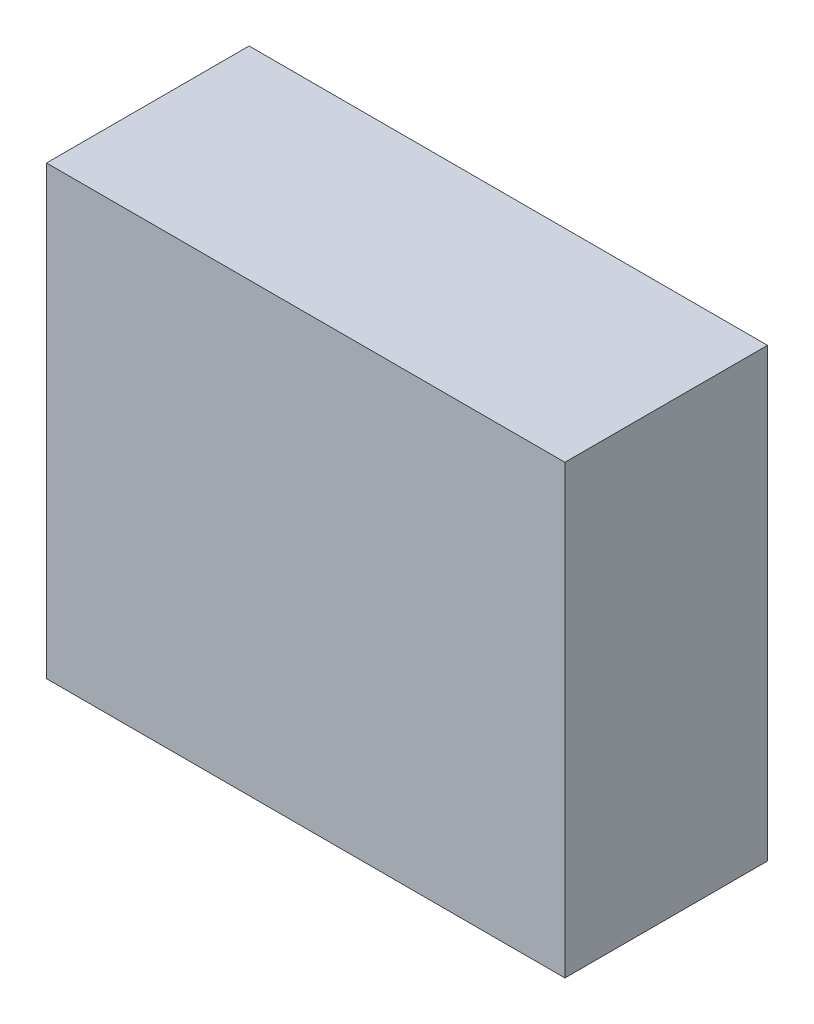
SolidWorks part; units mm, degrees
ref_plane "Front Plane" through (0, 0, 0) normal (0, 0, 1) x (1, 0, 0)
ref_plane "Top Plane" through (0, 0, 0) normal (0, 1, 0) x (1, 0, 0)
ref_plane "Right Plane" through (0, 0, 0) normal (1, 0, 0) x (0, 0, -1)
sketch "Sketch1" plane through (0, 0, 0) normal (0, 0, 1) x (1, 0, 0)
  line L1 (-32.5, 28) -> (32.5, 28)
  line L2 (-32.5, 28) -> (-32.5, -28)
  line L3 (-32.5, -28) -> (32.5, -28)
  line L4 (32.5, 28) -> (32.5, -28)
  line L5 (-32.5, 28) -> (32.5, -28) construction
  line L6 (-32.5, -28) -> (32.5, 28) construction
  point P0 (0, 0)
  dimension "D1" = 65
  dimension "D2" = 56
extrude "Boss-Extrude1" add sketch "Sketch1" along normal blind 25.4
